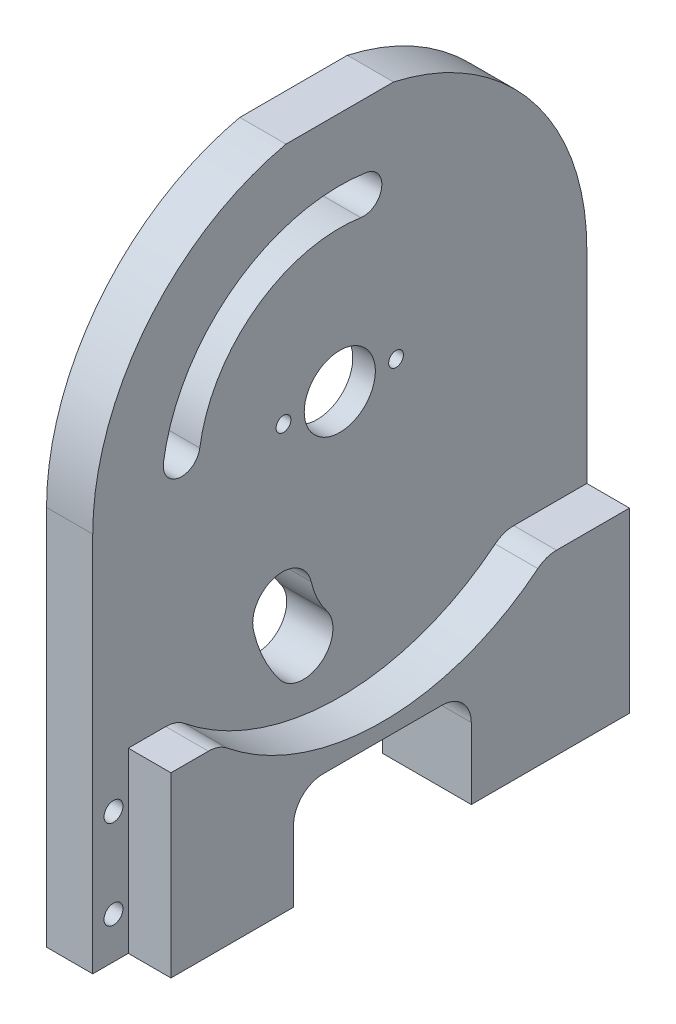
SolidWorks part; units mm, degrees
ref_plane "Front Plane" through (0, 0, 0) normal (0, 0, 1) x (1, 0, 0)
ref_plane "Top Plane" through (0, 0, 0) normal (0, 1, 0) x (1, 0, 0)
ref_plane "Right Plane" through (0, 0, 0) normal (1, 0, 0) x (0, 0, -1)
other "Configuration Table"
sketch "草图1" plane through (0, 0, 0) normal (0, 1, 0) x (1, 0, 0)
  line L0 (0, 0) -> (7.8, 0)
  line L1 (0, 0) -> (0, -83.4)
  line L2 (0, -83.4) -> (7.8, -83.4)
  line L3 (7.8, -83.4) -> (7.8, 0)
extrude "凸台-拉伸1" add sketch "草图1" along normal blind 105
sketch "草图2" plane through (0, 0, 0) normal (-1, 0, 0) x (0, 0, 1)
  line L0 (41.7, 0) -> (41.7, 105) construction
  line L1 (0, 0) -> (83.4, 0) construction
  line L2 (0, 105) -> (83.4, 105) construction
  line L3 (0, 64.3) -> (0, 105)
  line L4 (0, 105) -> (32.6226, 105)
  line L5 (83.4, 105) -> (83.4, 64.3)
  line L6 (50.7774, 105) -> (83.4, 105)
  arc A0 (83.4, 64.3) -> (50.7774, 105) centre (41.7, 64.3) ccw
  arc A1 (32.6226, 105) -> (0, 64.3) centre (41.7, 64.3) ccw
  dimension "D1" = 40.7
extrude "切除-拉伸1" cut sketch "草图2" against normal through all contours L3 L4 A1 | L6 L5 A0
sketch "草图3" plane through (0, 0, 0) normal (-1, 0, 0) x (0, 0, 1)
  line L0 (0, 64.3) -> (83.4, 64.3) construction
  circle A0 centre (41.7, 64.3) radius 6
  dimension "D1" = 12
extrude "切除-拉伸2" cut sketch "草图3" against normal through all
sketch "草图4" plane through (0, 0, 0) normal (-1, 0, 0) x (0, 0, 1)
  circle A0 centre (41.7, 64.3) radius 13.6
extrude "切除-拉伸3" cut sketch "草图4" against normal blind 4
sketch "草图5" plane through (4, 0, 0) normal (-1, 0, 0) x (0, 0, 1)
  line L0 (41.7, 64.3) -> (32.2, 64.3) construction
  line L1 (41.7, 64.3) -> (51.2, 64.3) construction
  circle A0 centre (32.2, 64.3) radius 1.25
  circle A1 centre (51.2, 64.3) radius 1.25
extrude "切除-拉伸4" cut sketch "草图5" against normal blind 4
sketch "草图6" plane through (7.8, 0, 0) normal (1, 0, 0) x (0, 0, -1)
  line L0 (-41.7, 64.3) -> (-41.7, 0) construction
  line L1 (-83.4, 0) -> (0, 0) construction
  line L2 (-83.4, 0) -> (0, 0)
  line L3 (0, 0) -> (0, 30)
  line L4 (0, 64.3) -> (-83.4, 64.3)
  line L5 (-83.4, 64.3) -> (-83.4, 61.3)
  line L6 (-83.4, 30) -> (-69.2536, 30)
  line L7 (-83.4, 30) -> (-83.4, 0)
  line L8 (0, 61.3) -> (0, 64.3)
  line L9 (-14.1464, 30) -> (0, 30)
  arc A0 (-69.2536, 30) -> (-14.1464, 30) centre (-41.7, 61.3) ccw
  arc A1 (0, 61.3) -> (-0.1081, 64.3) centre (-41.7, 61.3) ccw
  arc A2 (-83.2919, 64.3) -> (-83.4, 61.3) centre (-41.7, 61.3) ccw
  line M13 (-83.4, 64.3) -> (-83.4, 0)
  line M14 (-83.4, 0) -> (0, 0)
  line M15 (0, 0) -> (0, 64.3)
  dimension "D1" = 3
  dimension "D2" = 30
extrude "凸台-拉伸2" add sketch "草图6" along normal blind 7.2 contours A0 L0 L2 L9 M15 | L0 A0 L6 M13 M14
sketch "草图7" plane through (15, 0, 0) normal (1, 0, 0) x (0, 0, -1)
  line L0 (-83.4, 30) -> (-77.4, 30)
  line L1 (-83.4, 30) -> (-69.2536, 30) construction
  line L2 (-77.4, 30) -> (-77.4, 0)
  line L3 (-83.4, 0) -> (0, 0) construction
  line L4 (-77.4, 0) -> (-83.4, 0)
  line L5 (-83.4, 0) -> (-83.4, 30)
extrude "切除-拉伸5" cut sketch "草图7" against normal up to surface (7.2 mm away) up to face at (7.8, 64.3, 33.45)
sketch "草图8" plane through (0, 0, 0) normal (-1, 0, 0) x (0, 0, 1)
  line L1 (0, 0) -> (83.4, 0) construction
  line L2 (31.7, 17) -> (51.7, 17)
  line L3 (26.7, 12) -> (26.7, 0)
  line L4 (26.7, 0) -> (56.7, 0)
  line L5 (56.7, 0) -> (56.7, 12)
  arc A0 (56.7, 12) -> (51.7, 17) centre (51.7, 12) ccw
  arc A1 (31.7, 17) -> (26.7, 12) centre (31.7, 12) ccw
  point P7 (41.7, 17)
  dimension "D1" = 5
extrude "切除-拉伸6" cut sketch "草图8" against normal through all
sketch "草图9" plane through (0, 0, 0) normal (0, -1, 0) x (1, 0, 0)
  circle A0 centre (7.5, 73.4) radius 1.65
  circle A1 centre (7.5, 62.7) radius 1.65
  circle A2 centre (7.5, 20.7) radius 1.65
  circle A3 centre (7.5, 6) radius 1.65
extrude "切除-拉伸7" cut sketch "草图9" against normal blind 15
sketch "草图10" plane through (0, 0, 0) normal (-1, 0, 0) x (0, 0, 1)
  line L0 (41.7, 64.3) -> (68.3905, 68.2986) construction
  line L2 (41.7, 64.3) -> (37.2407, 94.0658) construction
  line L3 (68.3905, 68.2986) -> (71.4658, 68.7593) construction
  arc A4 (71.4658, 68.7593) -> (37.2407, 94.0658) centre (41.7, 64.3) ccw
  arc A5 (65.3342, 67.8407) -> (38.1593, 87.9342) centre (41.7, 64.3) ccw
  arc A6 (71.4658, 68.7593) -> (65.3342, 67.8407) centre (68.4, 68.3) cw
  arc A7 (37.2407, 94.0658) -> (38.1593, 87.9342) centre (37.7, 91) ccw
  dimension "D1" = 90
extrude "切除-拉伸8" cut sketch "草图10" against normal through all
fillet "圆角1" radius 5 2 edges at (11.4, 30, 14.1464) (11.4, 30, 69.2536)
sketch "草图15" plane through (0, 0, 0) normal (-1, 0, 0) x (0, 0, 1)
  line L0 (41.7, 64.3) -> (51.3968, 37.761) construction
  line L1 (41.7, 64.3) -> (47.8558, 30.2608) construction
  arc A0 (51.3968, 37.761) -> (47.8558, 30.2608) centre (32.3961, 42.1456) cw construction
  arc A1 (51.8198, 27.2134) -> (56.2688, 36.6367) centre (32.3961, 42.1456) ccw
  arc A2 (43.8918, 33.3082) -> (46.5248, 38.8852) centre (32.3961, 42.1456) ccw
  arc A3 (43.8918, 33.3082) -> (51.8198, 27.2134) centre (47.8558, 30.2608) ccw
  arc A4 (56.2688, 36.6367) -> (46.5248, 38.8852) centre (51.3968, 37.761) ccw
  point P4 (50.0297, 33.8204)
  dimension "D1" = 9.82
extrude "切除-拉伸10" cut sketch "草图15" against normal through all
sketch "草图16" plane through (0, 0, 0) normal (-1, 0, 0) x (0, 0, 1)
  line L0 (83.4, 0) -> (79.9, 0) construction
  line L1 (79.9, 0) -> (79.9, 30) construction
  line L2 (77.4, 30) -> (83.4, 30) construction
  circle A0 centre (79.9, 7) radius 1.6
  circle A1 centre (79.9, 22) radius 1.6
  dimension "D2" = 15
  dimension "D1" = 3.5
  dimension "D3" = 7
extrude "切除-拉伸11" cut sketch "草图16" against normal through all
sketch "草图17" plane through (0, 0, 0) normal (-1, 0, 0) x (0, 0, 1)
  circle A0 centre (79.9, 7) radius 3
  circle A1 centre (79.9, 22) radius 3
extrude "切除-拉伸12" cut sketch "草图17" against normal blind 2
